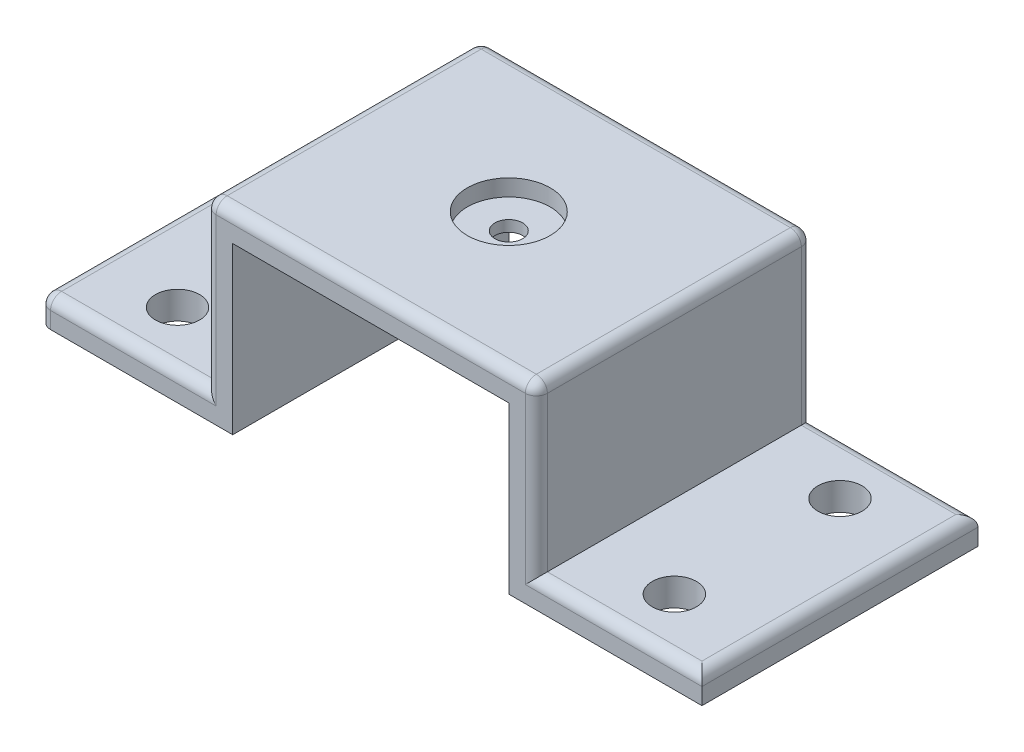
SolidWorks part; units mm, degrees
material "Cast Alloy Steel"
ref_plane "Front Plane" through (0, 0, 0) normal (0, 0, 1) x (1, 0, 0)
ref_plane "Top Plane" through (0, 0, 0) normal (0, 1, 0) x (1, 0, 0)
ref_plane "Right Plane" through (0, 0, 0) normal (1, 0, 0) x (0, 0, -1)
sketch "Sketch3" plane through (0, 0, 0) normal (0, 0, 1) x (1, 0, 0)
  line L0 (-95.6428, 38.1) -> (95.6428, 38.1) construction
  line L1 (-76.2, 38.1) -> (-38.1, 38.1)
  line L2 (-38.1, 38.1) -> (-38.1, 76.2)
  line L3 (-38.1, 76.2) -> (38.1, 76.2)
  line L4 (38.1, 76.2) -> (38.1, 38.1)
  line L5 (38.1, 38.1) -> (76.2, 38.1)
  point P4 (0, 38.1)
  point P9 (0, 76.2)
  dimension "D1" = 38.1
  dimension "D2" = 38.1
  dimension "D3" = 76.2
  dimension "D4" = 38.1
  dimension "D5" = 38.1
extrude "Extrude-Thin2" add sketch "Sketch3" along normal mid plane 63.5 thin
sketch "Sketch13" plane through (0, 76.2, 0) normal (0, 1, 0) x (1, 0, 0)
  point P0 (0, 0)
hole_wizard "CBORE for #00 Binding Head Machine Screw1" positions "Sketch13" profile "Sketch12" counterbore size "#00" standard "ANSI Inch" end condition through all
sketch "Sketch12" plane through (0, 76.2, 0) normal (1, 0, 0) x (0, 0, 1)
  line L0 (0, 0) -> (0, 44.45)
  line L1 (0, 44.45) -> (3.175, 44.45)
  line L3 (3.175, 44.45) -> (3.175, 3.81)
  line L4 (3.175, 3.81) -> (9.525, 3.81)
  line L5 (9.525, 3.81) -> (9.525, 0)
  line L7 (9.525, 0) -> (0, 0)
  line L11 (0, -6.35) -> (0, 107.95) construction
  dimension "Thru Hole Dia." = 6.35
  dimension "Thru Hole Depth" = 44.45
  dimension "C'Bore Dia." = 19.05
  dimension "C'Bore Depth" = 3.81
sketch "Sketch14" plane through (0, 38.1, 0) normal (0, 1, 0) x (1, 0, 0)
  line L0 (-76.2, -31.75) -> (-76.2, 31.75) construction
  line L1 (-76.2, -31.75) -> (-38.1, -31.75) construction
  circle A0 centre (-57.15, -19.05) radius 5.08
  dimension "D1" = 10.16
  dimension "D2" = 19.05
  dimension "D3" = 12.7
extrude "Cut-Extrude1" cut sketch "Sketch14" against normal through all
pattern_linear "LPattern1" count 2 spacing 38.1 along (0, 0, -1) count 2 spacing 114.3 along (1, 0, 0) of "Cut-Extrude1"
fillet "Fillet1" radius 2.54 15 edges at (-38.1, 76.2, 0) (-38.1, 57.15, -31.75) (38.1, 76.2, 0) (38.1, 57.15, -31.75) (-57.15, 38.1, -31.75) (0, 76.2, -31.75) (57.15, 38.1, -31.75) (57.15, 38.1, 31.75) (76.2, 38.1, 0) (38.1, 57.15, 31.75) (0, 76.2, 31.75) (-38.1, 57.15, 31.75) (-57.15, 38.1, 31.75) (-76.2, 38.1, 0) (-76.2, 34.925, 31.75)
